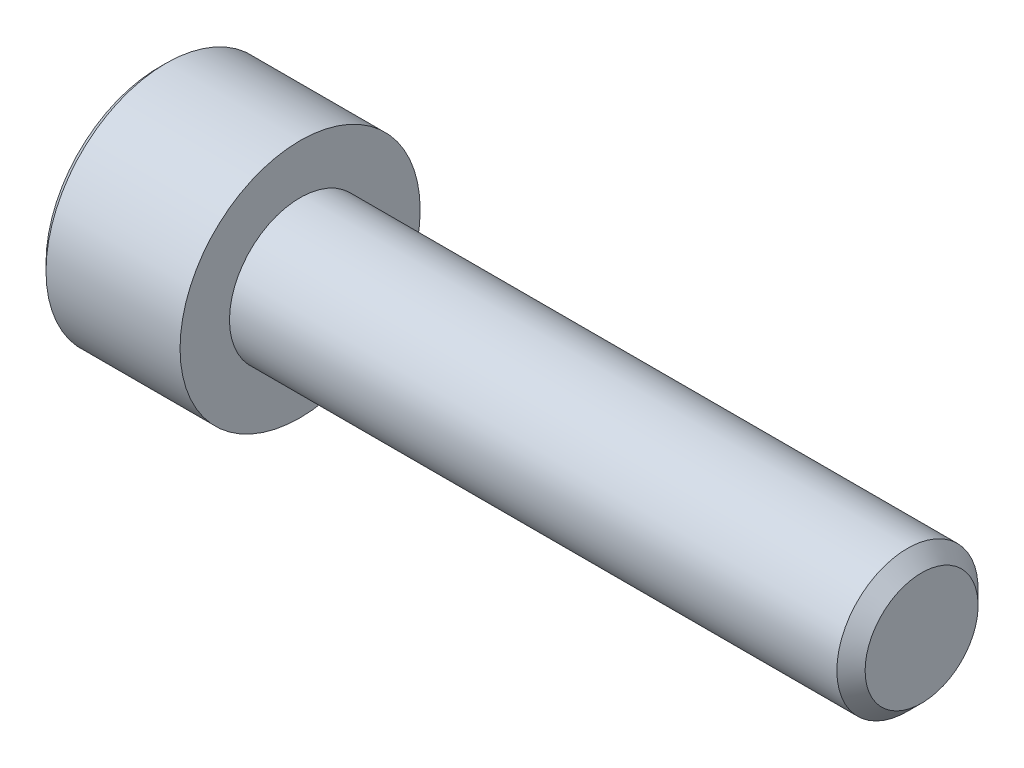
SolidWorks part; units mm, degrees
ref_plane "前视基准面" through (0, 0, 0) normal (0, 0, 1) x (1, 0, 0)
ref_plane "上视基准面" through (0, 0, 0) normal (0, 1, 0) x (1, 0, 0)
ref_plane "右视基准面" through (0, 0, 0) normal (1, 0, 0) x (0, 0, -1)
sketch "草图1" plane through (0, 0, 0) normal (0, 0, 1) x (1, 0, 0)
  line L0 (0, 0) -> (0, 2.5)
  line L1 (0, 2.5) -> (-22, 2.5)
  line L2 (-22, 2.5) -> (-22, 4.25)
  line L3 (-22, 4.25) -> (-27, 4.25)
  line L4 (-27, 4.25) -> (-27, 0)
  line L5 (-27, 0) -> (0, 0)
  line L6 (0, 0) -> (4.7488, 0) construction
  dimension "D1" = 5
  dimension "D2" = 22
  dimension "D3" = 5
  dimension "D4" = 8.5
revolve "旋转1" add sketch "草图1" angle 360 about L6
cosmetic thread "装饰螺纹线1" parameters "D1"=22, "D2"=4.3
chamfer "倒角1" distance 0.5 angle 45 1 edges at (0, 0, 2.5)
sketch "草图2" plane through (-27, 0, 0) normal (-1, 0, 0) x (0, 0, 1)
  line L1 (0, 2.3094) -> (-2, 1.1547)
  line L2 (-2, 1.1547) -> (-2, -1.1547)
  line L3 (-2, -1.1547) -> (0, -2.3094)
  line L4 (0, -2.3094) -> (2, -1.1547)
  line L5 (2, -1.1547) -> (2, 1.1547)
  line L6 (2, 1.1547) -> (0, 2.3094)
  circle A0 centre (0, 0) radius 2 construction
  dimension "D1" = 4
extrude "切除-拉伸1" cut sketch "草图2" against normal blind 2.5
chamfer "倒角2" distance 0.255 angle 45 1 edges at (-27, 0, 4.25)
sketch "草图4" plane through (-24.5, 0, 0) normal (-1, 0, 0) x (0, 0, 1)
  line L1 (0, -2.3094) -> (2, -1.1547)
  line L2 (2, -1.1547) -> (2, 1.1547)
  line L3 (2, 1.1547) -> (0, 2.3094)
  line L4 (0, 2.3094) -> (-2, 1.1547)
  line L5 (-2, 1.1547) -> (-2, -1.1547)
  line L6 (2, 1.1547) -> (0, 2.3094)
  line L7 (0, 2.3094) -> (-2, 1.1547)
  line L8 (-2, 1.1547) -> (-2, -1.1547)
  line L9 (-2, -1.1547) -> (0, -2.3094)
  line L10 (0, -2.3094) -> (2, -1.1547)
  line L11 (2, -1.1547) -> (2, 1.1547)
  line L12 (2, 1.1547) -> (0, 2.3094) construction
  line L13 (0, 2.3094) -> (-2, 1.1547) construction
  line L14 (-2, 1.1547) -> (-2, -1.1547) construction
  line L15 (-2, -1.1547) -> (0, -2.3094) construction
  line L16 (0, -2.3094) -> (2, -1.1547) construction
  line L17 (2, -1.1547) -> (2, 1.1547) construction
  line L18 (-2, -1.1547) -> (0, -2.3094)
  circle A0 centre (0, 0) radius 2 construction
  dimension "D1" = 0
extrude "切除-拉伸2" cut sketch "草图4" against normal through all draft 59
